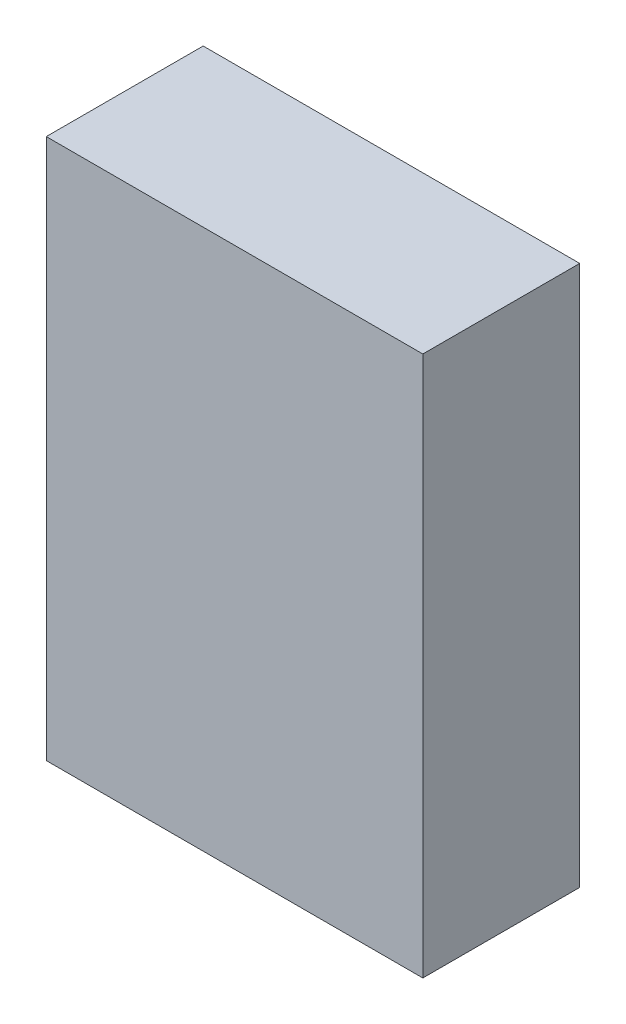
SolidWorks part; units mm, degrees
ref_plane "前视基准面" through (0, 0, 0) normal (0, 0, 1) x (1, 0, 0)
ref_plane "上视基准面" through (0, 0, 0) normal (0, 1, 0) x (1, 0, 0)
ref_plane "右视基准面" through (0, 0, 0) normal (1, 0, 0) x (0, 0, -1)
sketch "草图1" plane through (0, 0, 0) normal (0, 0, 1) x (1, 0, 0)
  line L0 (-0.54, -0.775) -> (0.54, -0.775)
  line L1 (0.54, -0.775) -> (0.54, 0.775)
  line L2 (0.54, 0.775) -> (-0.54, 0.775)
  line L3 (-0.54, 0.775) -> (-0.54, -0.775)
extrude "Component_Outline" add sketch "草图1" along normal blind 0.45 separate body
sketch3d "3D草图1"
  line L0 (0, 0, 0) -> (1, 0, 0)
  line L1 (0, 0, 0) -> (0, 1, 0)
  line L2 (0, 0, 0) -> (0, 0, 1)
  point P0 (0, 0, 0)
